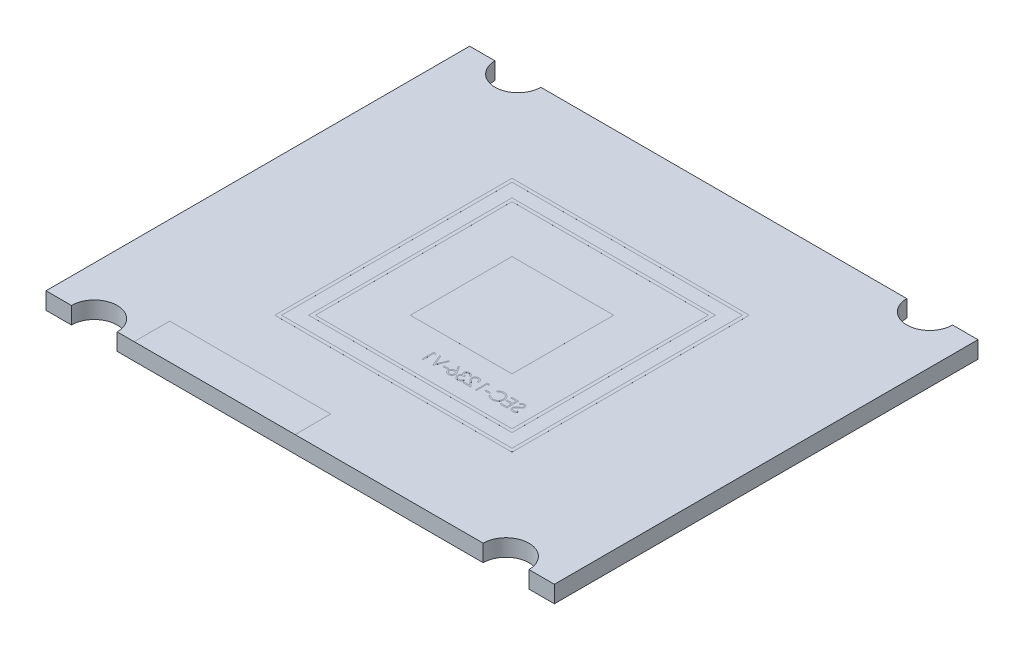
SolidWorks part; units mm, degrees
ref_plane "Plano frontal" through (0, 0, 0) normal (0, 0, 1) x (1, 0, 0)
ref_plane "Plano superior" through (0, 0, 0) normal (0, 1, 0) x (1, 0, 0)
ref_plane "Plano direito" through (0, 0, 0) normal (1, 0, 0) x (0, 0, -1)
sketch "Sketch1" plane through (0, 0, 0) normal (0, 1, 0) x (1, 0, 0)
  line L1 (-15, 12.5) -> (15, 12.5)
  line L2 (-15, 12.5) -> (-15, -12.5)
  line L3 (-15, -12.5) -> (15, -12.5)
  line L4 (15, 12.5) -> (15, -12.5)
  point P4 (0, 12.5)
  point P6 (-15, 0)
  dimension "D1" = 30
  dimension "D2" = 25
extrude "Boss-Extrude1" add sketch "Sketch1" along normal mid plane 1
sketch "Sketch2" plane through (0, 0, 0) normal (0, 1, 0) x (1, 0, 0)
  line L1 (-3, 3) -> (3, 3)
  line L2 (-3, 3) -> (-3, -3)
  line L3 (-3, -3) -> (3, -3)
  line L4 (3, 3) -> (3, -3)
  point P4 (0, 3)
  point P6 (-3, 0)
  dimension "D1" = 6
  dimension "D2" = 6
sketch "Sketch3" plane through (0, 0, 0) normal (0, 1, 0) x (1, 0, 0)
  line L0 (15, 12.5) -> (-15, 12.5) construction
  line L4 (-15, 12.5) -> (-15, -12.5) construction
  line L5 (0, -0.55) -> (0, 0.55) construction
  line L6 (-0.55, 0) -> (0.55, 0) construction
  circle A0 centre (-12.15, 12.5) radius 1.35
  circle A1 centre (12.15, 12.5) radius 1.35
  circle A2 centre (12.15, -12.5) radius 1.35
  circle A3 centre (-12.15, -12.5) radius 1.35
  dimension "D1" = 2.7
  dimension "D2" = 1.5
extrude "Cut-Extrude2" cut sketch "Sketch3" against normal through all both and the other way through all
extrude "Boss-Extrude2" add sketch "Sketch2" along normal mid plane 1.0001
sketch "Sketch4" plane through (0, -0.5, 0) normal (0, -1, 0) x (1, 0, 0)
  circle A0 centre (0, 0) radius 2.25
  dimension "D1" = 4.5
extrude "Boss-Extrude3" add sketch "Sketch4" along normal blind 2
sketch "Sketch5" plane through (0, -2.5001, 0) normal (0, -1, 0) x (1, 0, 0)
  circle A0 centre (0, 0) radius 0.5
  dimension "D1" = 1
extrude "Cut-Extrude3" cut sketch "Sketch5" against normal blind 0.4
sketch "Sketch6" plane through (0, -2.1, 0) normal (0, -1, 0) x (1, 0, 0)
  line L0 (-0.5, 0) -> (0.5, 0)
  circle A0 centre (0, 0) radius 0.5 construction
  circle A1 centre (0, 0) radius 0.5 construction
  arc A2 (0.5, 0) -> (-0.5, 0) centre (0, 0) ccw
revolve "Revolve1" add sketch "Sketch6" angle 180 about L0
chamfer "Chamfer1" distance 0.2 angle 45 3 edges at (0, -2.5001, -2.25) (0, -2.5001, -0.5) (0, -0.5, -2.25)
sketch "Sketch9" plane through (0, 0, 0) normal (0, 1, 0) x (1, 0, 0)
  line L0 (-10.8, -12.5) -> (10.8, -12.5) construction
  line L1 (-9.8, -10.4) -> (-0.3, -10.4)
  line L2 (-9.8, -10.4) -> (-9.8, -12.5)
  line L3 (-9.8, -12.5) -> (-0.3, -12.5)
  line L4 (-0.3, -10.4) -> (-0.3, -12.5)
  dimension "D1" = 9.5
  dimension "D2" = 1
  dimension "D3" = 2.1
extrude "Marcação Fios" add sketch "Sketch9" along normal mid plane 1.0001
sketch "Sketch10" plane through (0, 0, 0) normal (0, 1, 0) x (1, 0, 0)
  line L0 (-6, -6) -> (6, -6)
  line L1 (-5.8, -5.8) -> (5.8, -5.8)
  line L2 (-5.8, -5.8) -> (-5.8, 5.8)
  line L3 (-5.8, 5.8) -> (5.8, 5.8)
  line L4 (5.8, -5.8) -> (5.8, 5.8)
  line L5 (6, -6) -> (6, 6)
  line L6 (-6, 6) -> (6, 6)
  line L7 (-6, -6) -> (-6, 6)
  line L8 (6.8, 6.8) -> (-6.8, 6.8)
  line L9 (7, 7) -> (-7, 7)
  line L10 (7, 7) -> (7, -7)
  line L11 (7, -7) -> (-7, -7)
  line L12 (-7, 7) -> (-7, -7)
  line L13 (-6.8, 6.8) -> (-6.8, -6.8)
  line L14 (6.8, -6.8) -> (-6.8, -6.8)
  line L15 (6.8, 6.8) -> (6.8, -6.8)
  point P0 (0, 0)
  point P6 (0, 5.8)
  point P7 (5.8, 0)
  point P16 (0, -7)
  point P17 (7, 0)
  dimension "D1" = 12
  dimension "D2" = 12
  dimension "D4" = 14
  dimension "D5" = 14
extrude "Contorno Câmera" add sketch "Sketch10" along normal mid plane 1.001 contours L9 L12 L11 L10 L8 L15 L14 L13 | L7 L0 L5 L6 L4 L1 L2 L3
sketch "Sketch11" plane through (0, 0, 0) normal (0, 1, 0) x (1, 0, 0)
  text T0 "SEC-1236-V1" font "Century Gothic" height 0.7
extrude "Boss-Extrude6" add sketch "Sketch11" along normal mid plane 1.001
